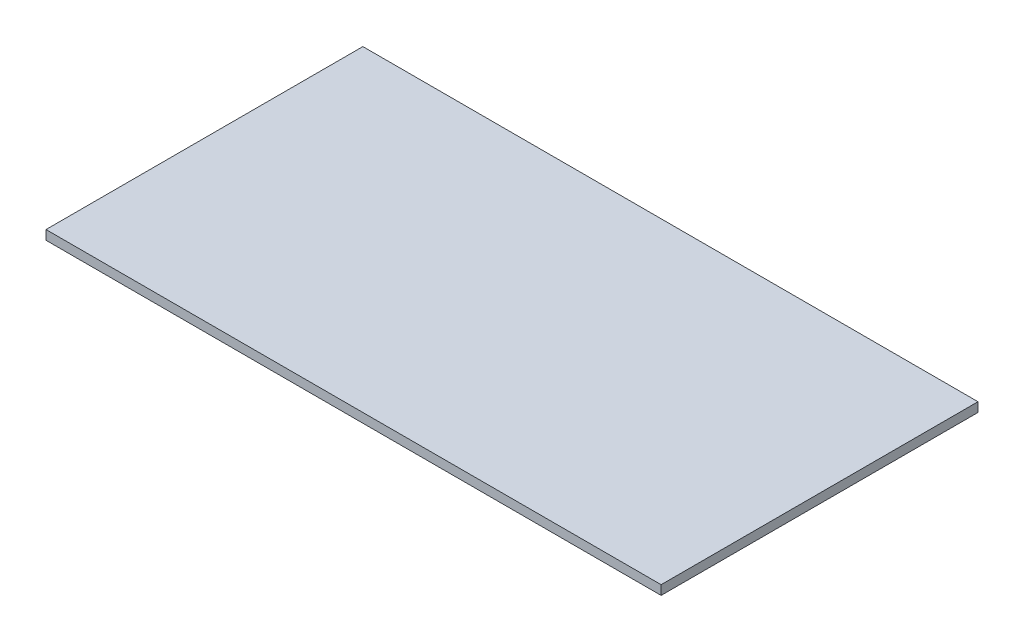
SolidWorks part; units mm, degrees
ref_plane "Front Plane" through (0, 0, 0) normal (0, 0, 1) x (1, 0, 0)
ref_plane "Top Plane" through (0, 0, 0) normal (0, 1, 0) x (1, 0, 0)
ref_plane "Right Plane" through (0, 0, 0) normal (1, 0, 0) x (0, 0, -1)
sketch "Sketch1" plane through (0, 0, 0) normal (0, 1, 0) x (1, 0, 0)
  line L1 (0, 0) -> (198, 0)
  line L2 (0, 0) -> (0, 102)
  line L3 (0, 102) -> (198, 102)
  line L4 (198, 0) -> (198, 102)
  dimension "D1" = 102
  dimension "D2" = 198
extrude "Boss-Extrude1" add sketch "Sketch1" along normal blind 3
